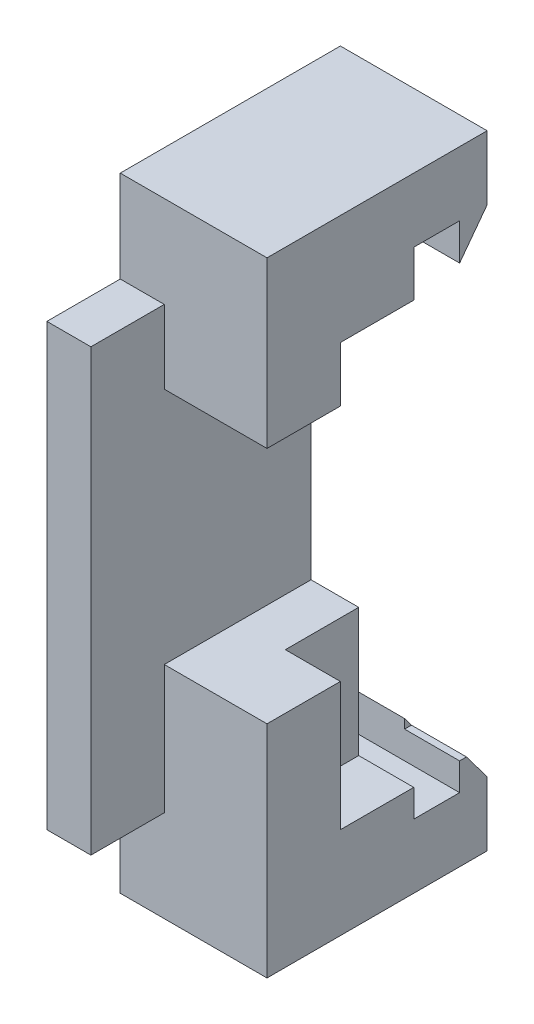
SolidWorks part; units mm, degrees
ref_plane "Front Plane" through (0, 0, 0) normal (0, 0, 1) x (1, 0, 0)
ref_plane "Top Plane" through (0, 0, 0) normal (0, 1, 0) x (1, 0, 0)
ref_plane "Right Plane" through (0, 0, 0) normal (1, 0, 0) x (0, 0, -1)
sketch "Sketch1" plane through (0, 0, 0) normal (0, 0, 1) x (1, 0, 0)
  line L1 (0, 0) -> (4, 0)
  line L2 (0, 0) -> (0, 17)
  line L3 (0, 17) -> (4, 17)
  line L4 (4, 0) -> (4, 17)
  dimension "D1" = 17
  dimension "D2" = 4
extrude "Boss-Extrude1" add sketch "Sketch1" along normal blind 6
sketch "Sketch2" plane through (0, 0, 6) normal (0, 0, 1) x (1, 0, 0)
  line L0 (4, 0) -> (4, 17) construction
  line L1 (4, 12.5) -> (1.2, 12.5)
  line L2 (4, 12.5) -> (4, 6)
  line L3 (4, 6) -> (1.2, 6)
  line L4 (1.2, 12.5) -> (1.2, 6)
  line L5 (4, 17) -> (0, 17) construction
  line L6 (0, 0) -> (4, 0) construction
  line L7 (0, 17) -> (0, 0) construction
  line L9 (4, 5.25) -> (2.5, 5.25)
  line L10 (4, 5.25) -> (4, 2.5)
  line L11 (4, 2.5) -> (2.5, 2.5)
  line L12 (2.5, 5.25) -> (2.5, 2.5)
  point P6 (2.6, 12.5)
  dimension "D1" = 4.5
  dimension "D2" = 6
  dimension "D3" = 1.2
  dimension "D4" = 1.5
  dimension "D5" = 2.5
  dimension "D6" = 0.75
extrude "Cut-Extrude1" cut sketch "Sketch2" against normal through all
sketch "Sketch3" plane through (0, 0, 0) normal (-1, 0, 0) x (0, 0, 1)
  line L0 (0, 15.25) -> (0.75, 14.25)
  line L1 (0, 17) -> (0, 0) construction
  line L2 (0.75, 14.25) -> (0.75, 15.25)
  line L3 (0.75, 15.25) -> (2, 15.25)
  line L4 (2, 15.25) -> (2, 1.75)
  line L5 (0, 15.25) -> (0, 1.75)
  line L6 (-999.8573, 8.5) -> (49000.1427, 8.5) construction
  line L7 (6, 17) -> (0, 17) construction
  line L8 (6, 17) -> (6, 0) construction
  line L9 (0.75, 1.75) -> (2, 1.75)
  line L10 (0.75, 2.75) -> (0.75, 1.75)
  line L11 (0, 1.75) -> (0.75, 2.75)
  point P4 (1.6836, 8.5)
  point P13 (1.0759, 14.978)
  point P17 (0, 8.5)
  point P18 (2, 8.5)
  dimension "D1" = 1.75
  dimension "D2" = 4
  dimension "D3" = 1.25
  dimension "D4" = 1.75
  dimension "D5" = 1
extrude "Cut-Extrude2" cut sketch "Sketch3" against normal through all
sketch "Sketch4" plane through (4, 0, 0) normal (1, 0, 0) x (0, 0, -1)
  line L0 (-2, 2.5) -> (-6, 2.5) construction
  line L1 (-6, 5.25) -> (-4, 5.25)
  line L2 (-6, 5.25) -> (-6, 2.5)
  line L3 (-6, 2.5) -> (-4, 2.5)
  line L4 (-4, 5.25) -> (-4, 2.5)
  dimension "D1" = 2
extrude "Boss-Extrude2" add sketch "Sketch4" against normal blind 2
sketch "Sketch5" plane through (0, 0, 6) normal (0, 0, 1) x (1, 0, 0)
  line L0 (0, 17) -> (0, 0) construction
  line L1 (0, 14.5) -> (1.2, 14.5)
  line L2 (0, 14.5) -> (0, 2.5)
  line L3 (0, 2.5) -> (1.2, 2.5)
  line L4 (1.2, 14.5) -> (1.2, 2.5)
  line L5 (0, 0) -> (4, 0) construction
  line L6 (4, 17) -> (0, 17) construction
  point P6 (0.6, 2.5)
  dimension "D1" = 2.5
  dimension "D2" = 2.5
  dimension "D3" = 1.2
extrude "Boss-Extrude3" add sketch "Sketch5" along normal blind 2
sketch "Sketch6" plane through (0, 0, 2) normal (0, 0, -1) x (-1, 0, 0)
  line L1 (-4, 12.5) -> (-2.5, 12.5)
  line L2 (-4, 12.5) -> (-4, 14)
  line L3 (-4, 14) -> (-2.5, 14)
  line L4 (-2.5, 12.5) -> (-2.5, 14)
  line L5 (-2.5, 5.25) -> (-4, 5.25)
  line L6 (-2.5, 5.25) -> (-2.5, 6)
  line L7 (-2.5, 6) -> (-4, 6)
  line L8 (-4, 5.25) -> (-4, 6)
  dimension "D1" = 1.5
  dimension "D2" = 1.5
extrude "Cut-Extrude3" cut sketch "Sketch6" against normal blind 2
